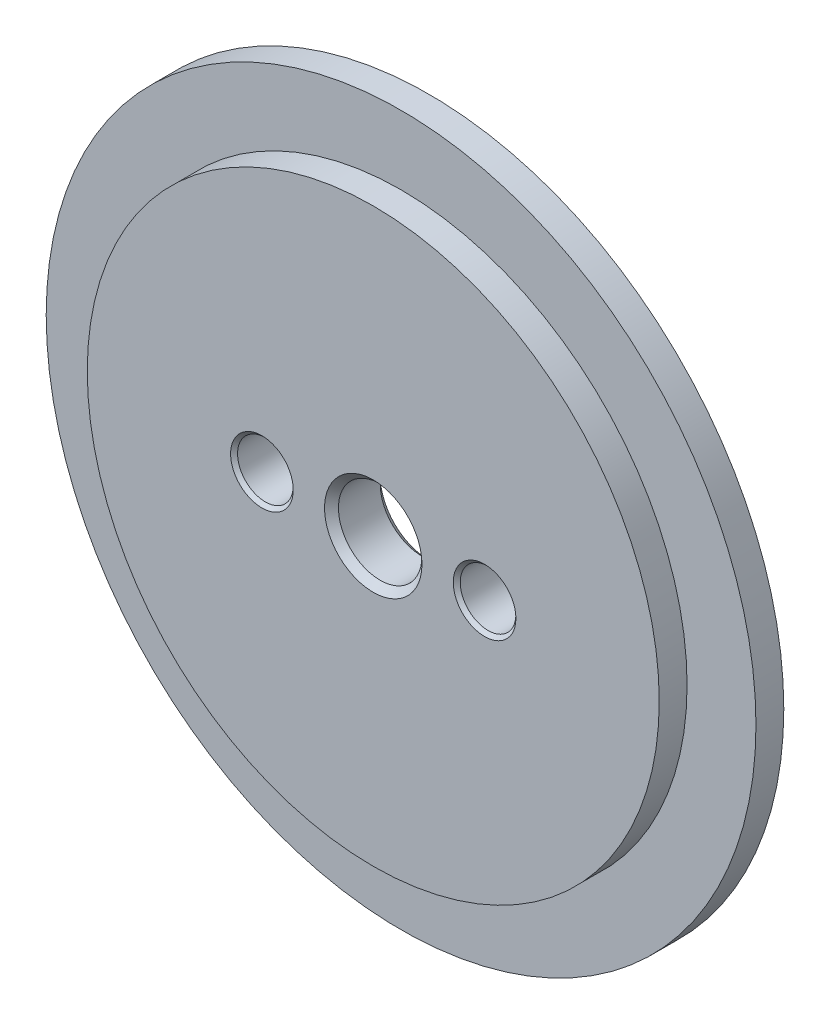
SolidWorks part; units mm, degrees
ref_plane "Front" through (0, 0, 0) normal (0, 0, 1) x (1, 0, 0)
ref_plane "Top" through (0, 0, 0) normal (0, 1, 0) x (1, 0, 0)
ref_plane "Right" through (0, 0, 0) normal (1, 0, 0) x (0, 0, -1)
sketch "Sketch1" plane through (0, 0, 0) normal (0, 0, 1) x (1, 0, 0)
  circle A0 centre (0, 0) radius 25.5
  dimension "D1" = 51
extrude "Boss-Extrude1" add sketch "Sketch1" along normal blind 2
sketch "Sketch2" plane through (0, 0, 2) normal (0, 0, 1) x (1, 0, 0)
  circle A0 centre (0, 0) radius 20.55
  circle A1 centre (0, 0) radius 25.5 construction
  dimension "D1" = 4.95
extrude "Boss-Extrude2" add sketch "Sketch2" along normal blind 2 contours A0
sketch "Sketch3" plane through (0, 0, 0) normal (0, 0, -1) x (-1, 0, 0)
  circle A5 centre (0, 0) radius 3
  circle A6 centre (8, 0) radius 2
  circle A7 centre (-8, 0) radius 2
  dimension "D1" = 6
  dimension "D2" = 4
  dimension "D3" = 4
  dimension "D4" = 8
  dimension "D5" = 8
extrude "Cut-Extrude1" cut sketch "Sketch3" against normal through all
chamfer "Chamfer1" distance 0.25 angle 45 2 edges at (6, 0, 0) (6, 0, 4)
chamfer "Chamfer2" distance 0.25 angle 45 2 edges at (-10, 0, 0) (-10, 0, 4)
chamfer "Chamfer3" distance 0.5 angle 45 2 edges at (-3, 0, 0) (-3, 0, 4)
